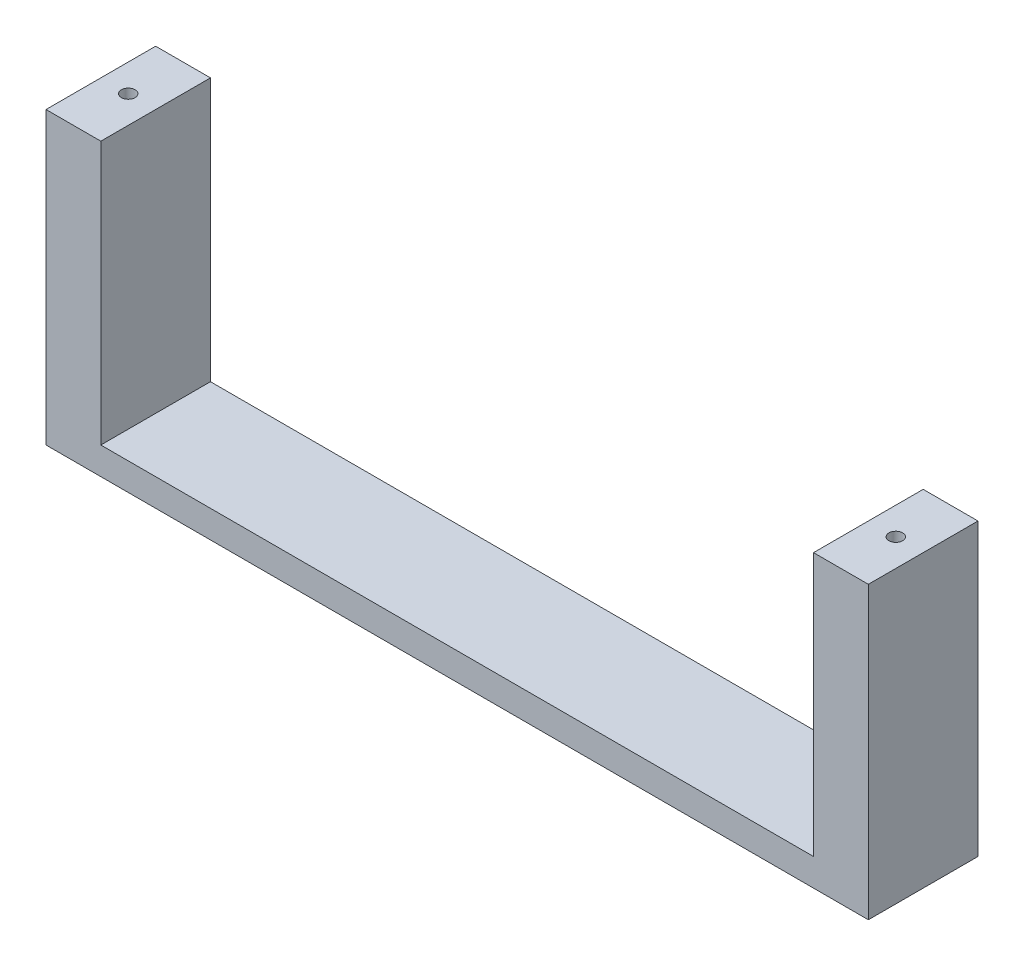
SolidWorks part; units mm, degrees
ref_plane "Alzado" through (0, 0, 0) normal (0, 0, 1) x (1, 0, 0)
ref_plane "Planta" through (0, 0, 0) normal (0, 1, 0) x (1, 0, 0)
ref_plane "Vista lateral" through (0, 0, 0) normal (1, 0, 0) x (0, 0, -1)
sketch "Croquis1" plane through (0, 0, 0) normal (0, 1, 0) x (1, 0, 0)
  line L1 (75, -10) -> (-75, -10)
  line L2 (75, -10) -> (75, 10)
  line L3 (75, 10) -> (-75, 10)
  line L4 (-75, -10) -> (-75, 10)
  line L5 (75, -10) -> (-75, 10) construction
  line L6 (75, 10) -> (-75, -10) construction
  point P0 (0, 0)
  dimension "D1" = 20
  dimension "D2" = 150
extrude "Saliente-Extruir1" add sketch "Croquis1" along normal blind 5
sketch "Croquis2" plane through (0, 5, 0) normal (0, 1, 0) x (1, 0, 0)
  line L0 (-75, -10) -> (75, -10) construction
  line L1 (75, 10) -> (65, 10)
  line L2 (75, 10) -> (75, -10)
  line L3 (75, -10) -> (65, -10)
  line L4 (65, 10) -> (65, -10)
  line L6 (-75, 10) -> (-65, 10)
  line L7 (-75, 10) -> (-75, -10)
  line L8 (-75, -10) -> (-65, -10)
  line L9 (-65, 10) -> (-65, -10)
  dimension "D1" = 10
  dimension "D2" = 10
extrude "Saliente-Extruir2" add sketch "Croquis2" along normal blind 48
sketch "Croquis3" plane through (0, 53, 0) normal (0, 1, 0) x (1, 0, 0)
  line L0 (70, 10) -> (70, -10) construction
  line L1 (75, 10) -> (65, 10) construction
  line L2 (65, -10) -> (75, -10) construction
  line L3 (75, 0) -> (-75, 0) construction
  line L4 (75, -10) -> (75, 10) construction
  line L5 (-75, 10) -> (-75, -10) construction
  line L6 (-70, 10) -> (-70, -10) construction
  line L7 (-65, 10) -> (-75, 10) construction
  line L8 (-75, -10) -> (-65, -10) construction
  circle A0 centre (-70, 0) radius 1.25
  circle A1 centre (70, 0) radius 1.25
  point P18 (-70, 0)
  point P19 (70, 0)
  dimension "D1" = 2.5
  dimension "D2" = 2.5
extrude "Cortar-Extruir1" cut sketch "Croquis3" against normal blind 10
